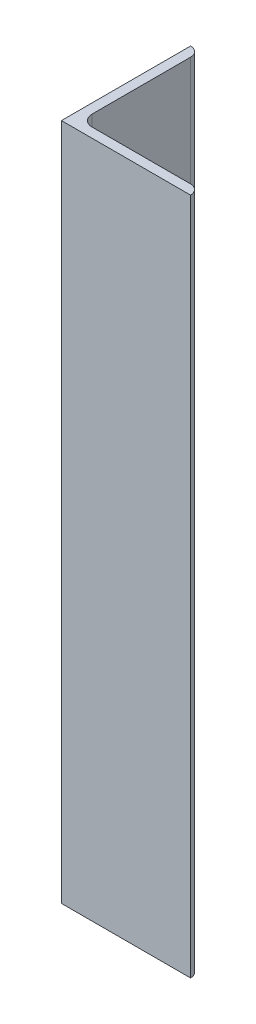
SolidWorks part; units mm, degrees
ref_plane "Front Plane" through (0, 0, 0) normal (0, 0, 1) x (1, 0, 0)
ref_plane "Top Plane" through (0, 0, 0) normal (0, 1, 0) x (1, 0, 0)
ref_plane "Right Plane" through (0, 0, 0) normal (1, 0, 0) x (0, 0, -1)
sketch3d "3DSketch1"
  line L0 (0, 0, 0) -> (0, 210, 0)
  dimension "D1" = 210
other "Iron V40X40X3(1)"
ref_plane "Plane1" through (0, 0, 0) normal (0, 1, 0) x (1, 0, 0)
sketch "Sketch11" plane through (0, 0, 0) normal (0, 1, 0) x (1, 0, 0)
  line L0 (0, 0) -> (0, 40)
  line L1 (0, 20) -> (3, 20) construction
  line L2 (3, 37) -> (3, 6.5)
  line L3 (6.5, 3) -> (37, 3)
  line L4 (20, 3) -> (20, 0) construction
  line L5 (40, 0) -> (0, 0)
  arc A0 (40, 0) -> (37, 3) centre (37, 0) ccw
  arc A1 (0, 40) -> (3, 37) centre (0, 37) cw
  arc A2 (6.5, 3) -> (3, 6.5) centre (6.5, 6.5) cw
  point P10 (20, 0)
  point P14 (0, 20)
  point P15 (3, 20)
  point P16 (20, 3)
  point P17 (3, 40)
  point P18 (40, 3)
  point P21 (0, 0)
  dimension "D2" = 3
  dimension "D3" = 40
  dimension "Radius_1" = 3.5
  dimension "D1" = 3
